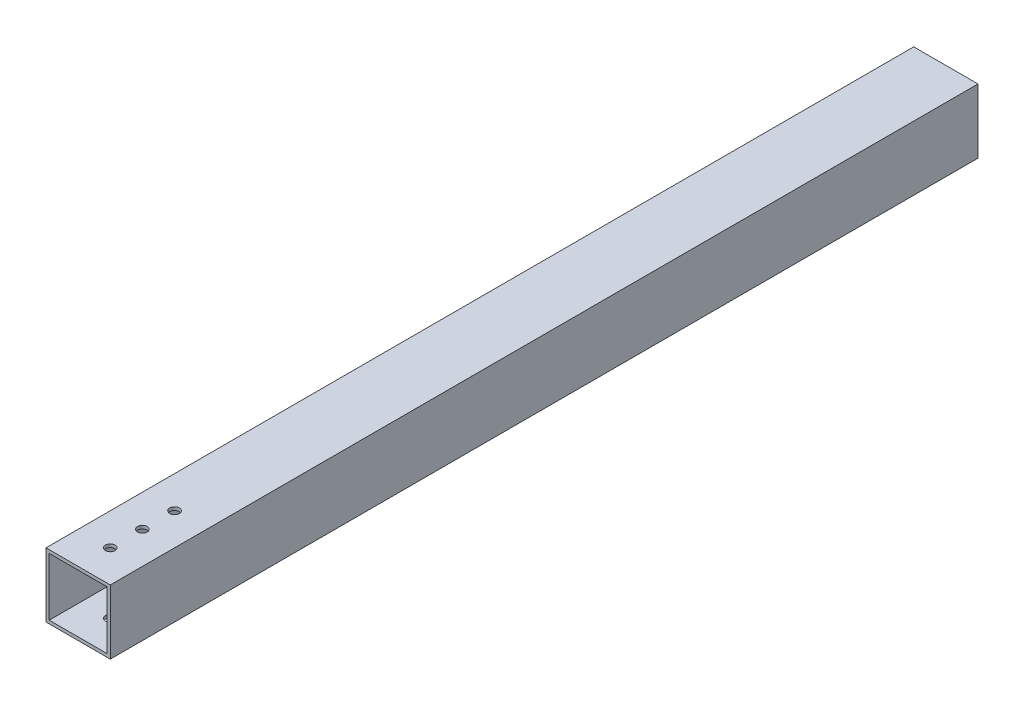
SolidWorks part; units mm, degrees
ref_plane "前视基准面" through (0, 0, 0) normal (0, 0, 1) x (1, 0, 0)
ref_plane "上视基准面" through (0, 0, 0) normal (0, 1, 0) x (1, 0, 0)
ref_plane "右视基准面" through (0, 0, 0) normal (1, 0, 0) x (0, 0, -1)
sketch "草图1" plane through (0, 0, 0) normal (0, 0, 1) x (1, 0, 0)
  line L1 (-9, 9) -> (9, 9)
  line L2 (-9, 9) -> (-9, -9)
  line L3 (-9, -9) -> (9, -9)
  line L4 (9, 9) -> (9, -9)
  line L5 (0, -9) -> (0, 9) construction
  line L6 (-9, 0) -> (9, 0) construction
  line L7 (-10, 10) -> (10, 10)
  line L8 (-10, 10) -> (-10, -10)
  line L9 (-10, -10) -> (10, -10)
  line L10 (10, 10) -> (10, -10)
  line L11 (0, -10) -> (0, 10) construction
  line L12 (-10, 0) -> (10, 0) construction
  point P0 (0, 0)
  point P4 (0, 0)
  dimension "D1" = 20
  dimension "D2" = 20
  dimension "D3" = 18
  dimension "D4" = 18
extrude "凸台-拉伸1" add sketch "草图1" along normal mid plane 270
sketch "草图2" plane through (0, 10, 0) normal (0, 1, 0) x (1, 0, 0)
  line L0 (0, -135) -> (0, 135) construction
  line L1 (10, -135) -> (-10, -135) construction
  line L2 (10, 135) -> (-10, 135) construction
  circle A0 centre (0, -125) radius 1.5
  circle A1 centre (0, -115) radius 1.5
  circle A2 centre (0, -105) radius 1.5
  dimension "D1" = 3
  dimension "D2" = 3
  dimension "D3" = 3
  dimension "D4" = 10
  dimension "D5" = 10
  dimension "D6" = 10
extrude "切除-拉伸1" cut sketch "草图2" against normal blind 100
